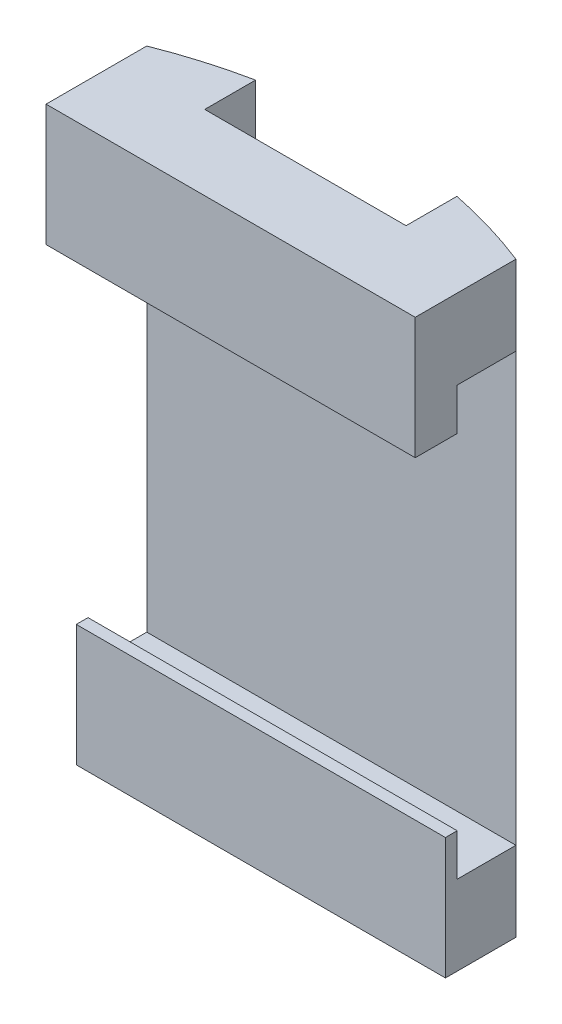
SolidWorks part; units mm, degrees
ref_plane "Front Plane" through (0, 0, 0) normal (0, 0, 1) x (1, 0, 0)
ref_plane "Top Plane" through (0, 0, 0) normal (0, 1, 0) x (1, 0, 0)
ref_plane "Right Plane" through (0, 0, 0) normal (1, 0, 0) x (0, 0, -1)
sketch "Sketch1" plane through (0, 0, 0) normal (0, 1, 0) x (1, 0, 0)
  line L0 (-11, 27.9106) -> (11, 27.9106)
  arc A0 (11, 27.9106) -> (-11, 27.9106) centre (0, 0) ccw
  dimension "D1" = 60
  dimension "D2" = 22
extrude "Boss-Extrude1" add sketch "Sketch1" along normal blind 35
sketch "Sketch2" plane through (0, 0, -27.9106) normal (0, 0, 1) x (1, 0, 0)
  line L0 (11, 35) -> (11, 0) construction
  line L1 (-11, 35) -> (11, 35)
  line L2 (-11, 35) -> (-11, 30.25)
  line L3 (-11, 30.25) -> (11, 30.25)
  line L4 (11, 35) -> (11, 30.25)
  line L5 (-11, 35) -> (-11, 0) construction
  line L6 (-11, 4.75) -> (11, 4.75)
  line L7 (-11, 4.75) -> (-11, 0)
  line L8 (-11, 0) -> (11, 0)
  line L9 (11, 4.75) -> (11, 0)
  dimension "D1" = 25.5
extrude "Boss-Extrude2" add sketch "Sketch2" along normal blind 6
sketch "Sketch3" plane through (-11, 0, 0) normal (-1, 0, 0) x (0, 0, 1)
  line L0 (-27.9106, 30.25) -> (-27.9106, 4.75) construction
  line L1 (-21.9106, 30.25) -> (-24.4106, 30.25)
  line L2 (-21.9106, 30.25) -> (-21.9106, 27.75)
  line L3 (-21.9106, 27.75) -> (-24.4106, 27.75)
  line L4 (-24.4106, 30.25) -> (-24.4106, 27.75)
  line L5 (-21.9106, 4.75) -> (-24.4106, 4.75)
  line L6 (-21.9106, 4.75) -> (-21.9106, 7.25)
  line L7 (-21.9106, 7.25) -> (-24.4106, 7.25)
  line L8 (-24.4106, 4.75) -> (-24.4106, 7.25)
  dimension "D1" = 3.5
  dimension "D2" = 3.5
  dimension "D3" = 2.5
extrude "Boss-Extrude3" add sketch "Sketch3" against normal through all
sketch "Sketch4" plane through (0, 0, -21.9106) normal (0, 0, 1) x (1, 0, 0)
  line L1 (-11, 7.25) -> (11, 7.25)
  line L2 (-11, 7.25) -> (-11, 0)
  line L3 (-11, 0) -> (11, 0)
  line L4 (11, 7.25) -> (11, 0)
extrude "Cut-Extrude1" cut sketch "Sketch4" against normal blind 1.8
sketch "Sketch5" plane through (0, 35, 0) normal (0, 1, 0) x (1, 0, 0)
  line L0 (11, 21.9106) -> (-11, 21.9106) construction
  line L2 (-6, 26.3645) -> (6, 26.3645)
  line L3 (-6, 26.3645) -> (-6, 31.7224)
  line L4 (-6, 31.7224) -> (6, 31.7224)
  line L5 (6, 26.3645) -> (6, 31.7224)
  point P4 (0, 26.3645)
  point P6 (0, 21.9106)
  dimension "D1" = 12
extrude "Cut-Extrude2" cut sketch "Sketch5" against normal blind 9.8
